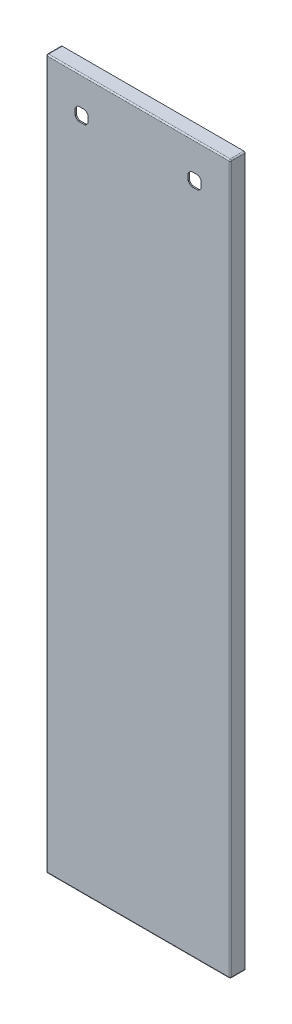
SolidWorks part; units mm, degrees
material "1.4301 (X5CrNi18-10)"
ref_plane "Ebene1" through (0, 0, 0) normal (0, 0, 1) x (1, 0, 0)
ref_plane "Ebene2" through (0, 0, 0) normal (0, 1, 0) x (1, 0, 0)
ref_plane "Ebene3" through (0, 0, 0) normal (1, 0, 0) x (0, 0, -1)
sketch "Skizze1" plane through (0, 0, 0) normal (0, 0, 1) x (1, 0, 0)
  line L1 (-142.5, 0) -> (142.5, 0)
  line L2 (-142.5, 0) -> (-142.5, 1098)
  line L3 (-142.5, 1098) -> (142.5, 1098)
  line L4 (142.5, 0) -> (142.5, 1098)
  dimension "D1" = 285
  dimension "D2" = 1098
extrude "Basis-Linear austragen" add sketch "Skizze1" against normal blind 23
shell "Wandung1" thickness 2
fillet "Verrundung1" radius 2 8 edges at (0, 1098, 0) (142.5, 549, 0) (0, 0, 0) (-142.5, 549, 0) (-142.5, 1098, -11.5) (142.5, 1098, -11.5) (142.5, 0, -11.5) (-142.5, 0, -11.5)
sketch "Skizze2" plane through (0, 0, 0) normal (0, 0, 1) x (1, 0, 0)
  line L0 (-140.5, 1098) -> (140.5, 1098) construction
  line L1 (-142.5, 2) -> (-142.5, 1096) construction
  line L3 (-92.5557, 1053.05) -> (-82.4443, 1053.05)
  line L4 (-97.55, 1048.0557) -> (-97.55, 1037.9443)
  line L5 (-92.5557, 1032.95) -> (-82.4443, 1032.95)
  line L6 (-77.45, 1048.0557) -> (-77.45, 1037.9443)
  arc A0 (-92.5557, 1053.05) -> (-97.55, 1048.0557) centre (-87.5, 1043) ccw
  arc A1 (-77.45, 1048.0557) -> (-82.4443, 1053.05) centre (-87.5, 1043) ccw
  arc A2 (-82.4443, 1032.95) -> (-77.45, 1037.9443) centre (-87.5, 1043) ccw
  arc A3 (-97.55, 1037.9443) -> (-92.5557, 1032.95) centre (-87.5, 1043) ccw
  dimension "D3" = 22.5
  dimension "D1" = 55
  dimension "D2" = 55
  dimension "D4" = 20.1
  dimension "D5" = 20.1
  dimension "D6" = 10.05
  dimension "D7" = 10.05
extrude "Schnitt-Linear austragen1" cut sketch "Skizze2" against normal up to next
sketch "Skizze3" plane through (0, 0, 0) normal (0, -1, 0) x (1, 0, 0)
  line L1 (-89.5, -7.9) -> (-79.7, -7.9)
  line L2 (-142.5, -23) -> (-142.5, -2) construction
  line L3 (-89.5, -14.1) -> (-79.7, -14.1)
  arc A0 (-79.7, -14.1) -> (-79.7, -7.9) centre (-79.7, -11) ccw
  arc A2 (-89.5, -7.9) -> (-89.5, -14.1) centre (-89.5, -11) ccw
  dimension "D2" = 9.8
  dimension "D1" = 53
  dimension "D3" = 11
  dimension "D4" = 6.2
extrude "Schnitt-Linear austragen2" cut sketch "Skizze3" against normal up to next
mirror "Spiegeln1" about plane through (0, 0, 0) normal (1, 0, 0) of "Schnitt-Linear austragen2", "Schnitt-Linear austragen1"
